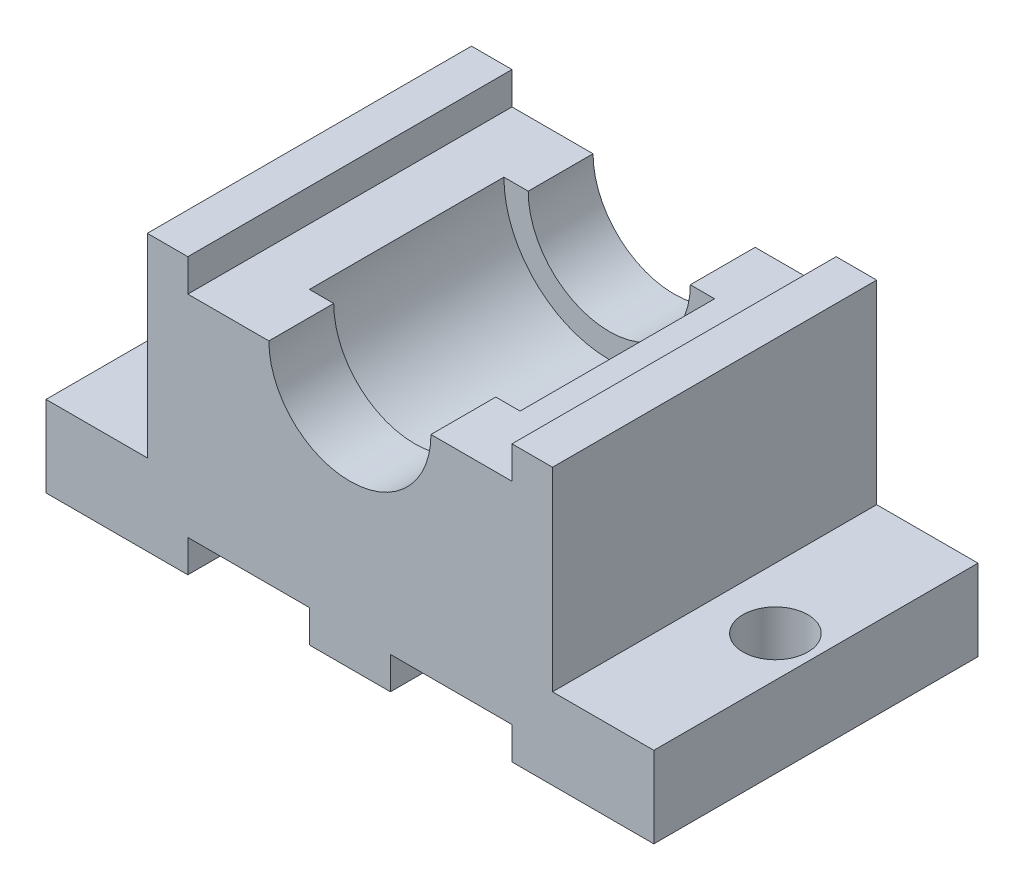
SolidWorks part; units mm, degrees
ref_plane "前视基准面" through (0, 0, 0) normal (0, 0, 1) x (1, 0, 0)
ref_plane "上视基准面" through (0, 0, 0) normal (0, 1, 0) x (1, 0, 0)
ref_plane "右视基准面" through (0, 0, 0) normal (1, 0, 0) x (0, 0, -1)
other "Configuration Table"
sketch "草图1" plane through (0, 0, 0) normal (0, 0, 1) x (1, 0, 0)
  line L0 (-5, 0) -> (5, 0)
  line L1 (5, 0) -> (5, 4)
  line L2 (5, 4) -> (20, 4)
  line L3 (20, 4) -> (20, 0)
  line L4 (20, 0) -> (37.5, 0)
  line L5 (37.5, 0) -> (37.5, 10)
  line L6 (37.5, 10) -> (25, 10)
  line L7 (25, 10) -> (25, 34)
  line L8 (25, 34) -> (20, 34)
  line L9 (20, 34) -> (20, 30)
  line L10 (20, 30) -> (10, 30)
  line L11 (0, 0) -> (0, 44.6062) construction
  line L12 (-20, 30) -> (-10, 30)
  line L13 (-20, 34) -> (-20, 30)
  line L14 (-25, 34) -> (-20, 34)
  line L15 (-25, 10) -> (-25, 34)
  line L16 (-37.5, 10) -> (-25, 10)
  line L17 (-37.5, 0) -> (-37.5, 10)
  line L18 (-20, 0) -> (-37.5, 0)
  line L19 (-20, 4) -> (-20, 0)
  line L20 (-5, 4) -> (-20, 4)
  line L21 (-5, 0) -> (-5, 4)
  arc A0 (-10, 30) -> (10, 30) centre (0, 30) ccw
  dimension "D1" = 10
  dimension "D9" = 10
  dimension "D2" = 40
  dimension "D3" = 34
  dimension "D4" = 4
  dimension "D5" = 10
  dimension "D6" = 50
  dimension "D7" = 75
  dimension "D8" = 4
  dimension "D10" = 40
extrude "凸台-拉伸1" add sketch "草图1" along normal mid plane 40
sketch "草图2" plane through (0, 0, 0) normal (0, 0, 1) x (1, 0, 0)
  circle A0 centre (0, 30) radius 13
  arc A1 (-10, 30) -> (10, 30) centre (0, 30) ccw construction
  dimension "D1" = 26
extrude "切除-拉伸1" cut sketch "草图2" against normal mid plane 24
sketch "草图3" plane through (0, 10, 0) normal (0, 1, 0) x (1, 0, 0)
  line L0 (0, 0) -> (0, 9.7569) construction
  circle A0 centre (-32.5, 0) radius 4
  circle A1 centre (32.5, 0) radius 4
  dimension "D1" = 8
  dimension "D2" = 65
extrude "切除-拉伸2" cut sketch "草图3" against normal through all
